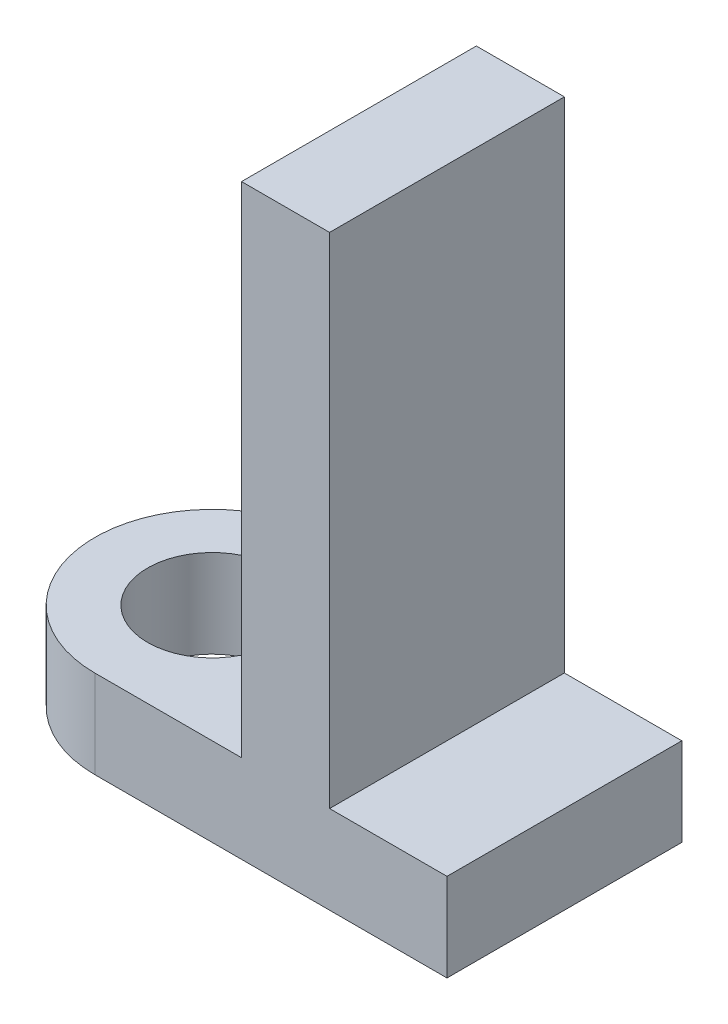
SolidWorks part; units mm, degrees
ref_plane "Ön Düzlem" through (0, 0, 0) normal (0, 0, 1) x (1, 0, 0)
ref_plane "Üst Düzlem" through (0, 0, 0) normal (0, 1, 0) x (1, 0, 0)
ref_plane "Sağ Düzlem" through (0, 0, 0) normal (1, 0, 0) x (0, 0, -1)
sketch "Çizim1" plane through (0, 0, 0) normal (0, 1, 0) x (1, 0, 0)
  line L0 (-45.0319, 227.9815) -> (554.9681, 227.9815)
  line L1 (-45.0319, -172.0185) -> (554.9681, -172.0185)
  line L2 (554.9681, 227.9815) -> (554.9681, -172.0185)
  circle A1 centre (-45.0319, 27.9815) radius 110
  arc A2 (-45.0319, 227.9815) -> (-45.0319, -172.0185) centre (-45.0319, 27.9815) ccw
  point P7 (0, 0)
  dimension "D1" = 600
  dimension "D2" = 600
extrude "Yükseklik-Ekstrüzyon1" add sketch "Çizim1" along normal blind 150
sketch "Çizim4" plane through (0, 150, 0) normal (0, 1, 0) x (1, 0, 0)
  line L0 (554.9681, 27.9815) -> (354.9681, 27.9815) construction
  line L1 (554.9681, -172.0185) -> (554.9681, 227.9815) construction
  line L2 (354.9681, 27.9815) -> (354.9681, 227.9815)
  line L3 (554.9681, 227.9815) -> (-45.0319, 227.9815) construction
  line L4 (354.9681, 227.9815) -> (204.9681, 227.9815)
  line L5 (204.9681, 227.9815) -> (204.9681, -172.0185)
  line L6 (-45.0319, -172.0185) -> (554.9681, -172.0185) construction
  line L7 (204.9681, -172.0185) -> (354.9681, -172.0185)
  line L8 (354.9681, -172.0185) -> (354.9681, 27.9815)
  dimension "D1" = 150
  dimension "D2" = 200
extrude "Yükseklik-Ekstrüzyon2" add sketch "Çizim4" along normal blind 850
sketch "Çizim5" plane through (0, 0, 172.0185) normal (0, 0, 1) x (1, 0, 0)
  line L0 (554.9681, 150) -> (554.9681, 350)
  circle A0 centre (554.9681, 350) radius 200
